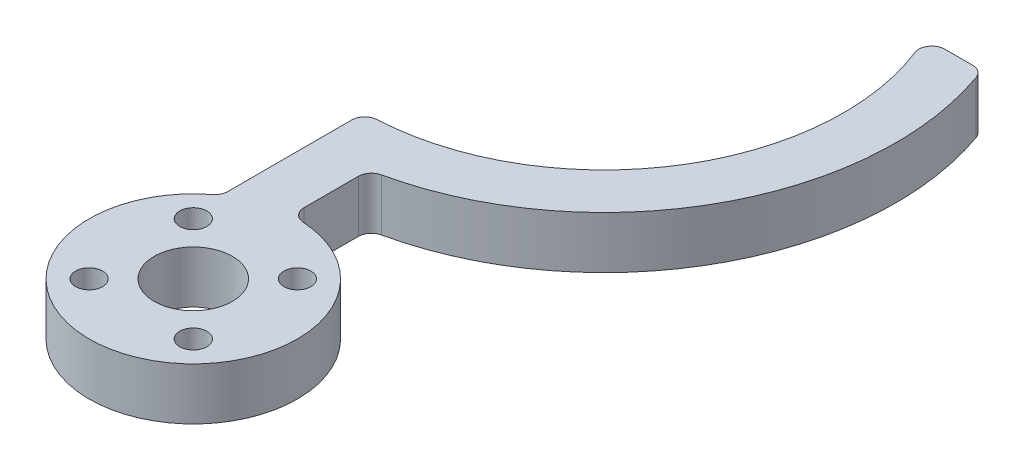
SolidWorks part; units mm, degrees
ref_plane "Front Plane" through (0, 0, 0) normal (0, 0, 1) x (1, 0, 0)
ref_plane "Top Plane" through (0, 0, 0) normal (0, 1, 0) x (1, 0, 0)
ref_plane "Right Plane" through (0, 0, 0) normal (1, 0, 0) x (0, 0, -1)
sketch "Sketch1" plane through (0, 0, 0) normal (0, 1, 0) x (1, 0, 0)
  line L0 (0, 44.83) -> (0, 36.83)
  line L1 (0, -36.83) -> (0, -46.83)
  line L2 (0, -46.83) -> (0, -58.83)
  line L3 (8, -44.1104) -> (8, -56.1104)
  line L8 (16.967, -80.0812) -> (0.967, -80.0812) construction
  line L13 (16.967, -80.0812) -> (16.967, -64.0812) construction
  line L21 (16.967, -64.0812) -> (0.967, -64.0812) construction
  line L22 (0.967, -80.0812) -> (0.967, -64.0812) construction
  line L23 (16.967, -80.0812) -> (0.967, -64.0812) construction
  line L24 (16.967, -64.0812) -> (0.967, -80.0812) construction
  arc A0 (0, -36.83) -> (0, 36.83) centre (0, 0) ccw
  arc A1 (8, -44.1104) -> (0, 44.83) centre (0, 0) ccw
  arc A7 (0, -58.83) -> (23.0776, -79.6236) centre (8.967, -72.0812) ccw
  circle A8 centre (0.967, -64.0812) radius 2.075
  circle A9 centre (16.967, -64.0812) radius 2.075
  circle A10 centre (16.967, -80.0812) radius 2.075
  circle A11 centre (0.967, -80.0812) radius 2.075
  arc A12 (0, -58.83) -> (8, -56.1104) centre (8.967, -72.0812) ccw
  circle A13 centre (8.967, -72.0812) radius 6.0032
  dimension "D1" = 73.66
  dimension "D8" = 4.15
  dimension "D6" = 16
  dimension "D2" = 8
  dimension "D3" = 8
  dimension "D4" = 12
  dimension "D9" = 10
  dimension "D7" = 16
  dimension "D5" = 12
extrude "Boss-Extrude2" add sketch "Sketch1" along normal blind 8 contours A7 A12 L3 A1 L0 A0 L1 L2 A8 A9 A10 A11
fillet "Fillet1" radius 2 6 edges at (0, 4, -36.83) (0, 4, -44.83) (8, 4, 56.1104) (8, 4, 44.1104) (0, 4, 58.83) (0, 4, 36.83)
sketch "Sketch2" plane through (0, 8, 0) normal (0, 1, 0) x (1, 0, 0)
  line L0 (0, 44.7833) -> (0, -43.796) construction
  line L1 (9.5729, -43.796) -> (0, -43.796) construction
  line L2 (0, -38.7785) -> (0, -57.8079) construction
  line L3 (0, 16.204) -> (0, -43.796) construction
  line L4 (0, 16.204) -> (41.799, 16.204) construction
  line L5 (41.799, 16.204) -> (33.0738, 16.204)
  line L6 (0, 42.7833) -> (0, 38.7785)
  line L8 (0, 44.7833) -> (0, 42.7833)
  line L9 (2.7521, 44.7829) -> (2.7521, 46.6557)
  line L10 (2.7521, 46.6557) -> (-0.2578, 46.6557)
  line L11 (-0.2578, 46.6557) -> (0, 44.7833)
  arc A0 (9.5729, -43.796) -> (2.0934, 44.7811) centre (0, 0) ccw construction
  arc A1 (1.897, -36.7811) -> (1.897, 36.7811) centre (0, 0) ccw construction
  arc A2 (2.7521, 44.7829) -> (41.799, 16.204) centre (2.3579, 3.2803) cw
  arc A3 (2.0934, 44.7811) -> (0, 42.7833) centre (2, 42.7833) ccw construction
  arc A4 (33.0738, 16.204) -> (1.897, 36.7811) centre (0, 0) ccw
  arc A6 (1.897, 36.7811) -> (0, 38.7785) centre (2, 38.7785) cw
extrude "Cut-Extrude1" cut sketch "Sketch2" against normal blind 19
fillet "Fillet2" radius 2 2 edges at (41.799, 4, -16.204) (33.0738, 4, -16.204)
equation "\"innerSmall\"= 2.9in"
equation "\"thick\"= 8mm"
equation "\"D1@Sketch1\"=\"innerSmall\""
equation "\"D2@Sketch1\"=\"thick\""
equation "\"D3@Sketch1\"=\"thick\""
equation "\"D7@Sketch1\"=16mm"
equation "\"hole pattern\"= 16mm"
equation "\"D1@Sketch4\"=\"hole pattern\""
equation "\"hole size\"= 4.25mm"
equation "\"D2@Sketch4\"=\"hole size\""
equation "\"D3@Sketch4\"=\"hole size\""
equation "\"D4@Sketch4\"=\"hole size\""
equation "\"discenter\"= 3mm"
equation "\"size\"= 9mm"
equation "\"D7@Sketch4\"=\"discenter\""
